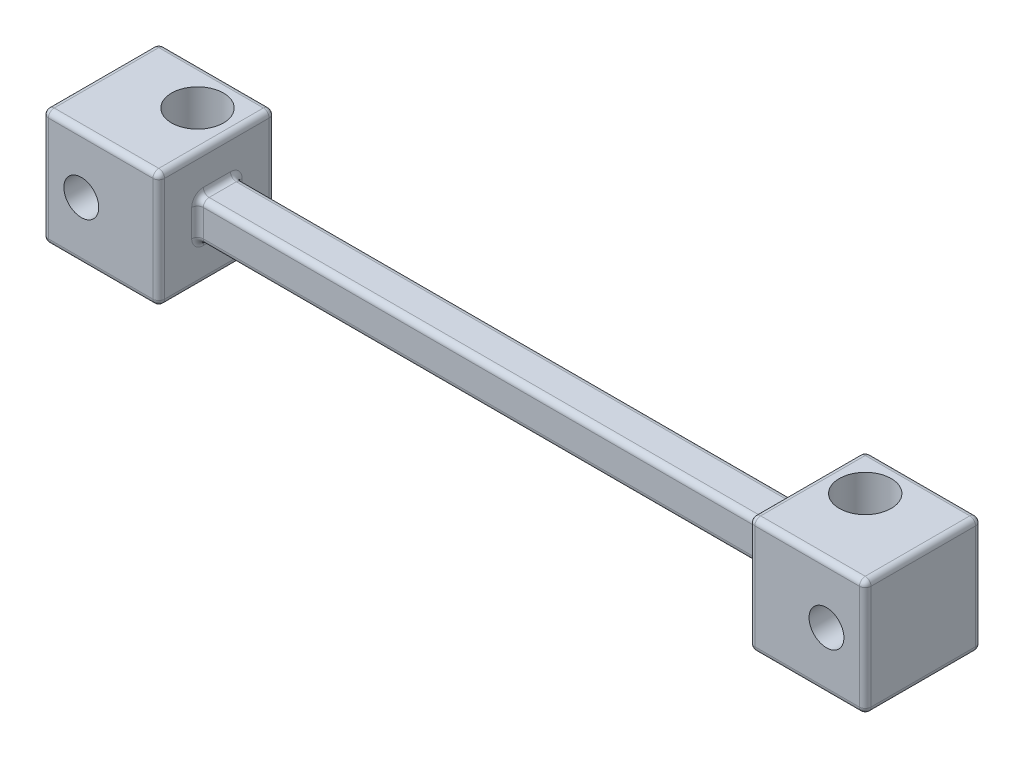
SolidWorks part; units mm, degrees
ref_plane "Front Plane" through (0, 0, 0) normal (0, 0, 1) x (1, 0, 0)
ref_plane "Top Plane" through (0, 0, 0) normal (0, 1, 0) x (1, 0, 0)
ref_plane "Right Plane" through (0, 0, 0) normal (1, 0, 0) x (0, 0, -1)
sketch "Sketch1" plane through (0, 0, 0) normal (1, 0, 0) x (0, 0, -1)
  line L1 (0, 0) -> (30, 0)
  line L2 (0, 0) -> (0, 30)
  line L3 (0, 30) -> (30, 30)
  line L4 (30, 0) -> (30, 30)
  dimension "D1" = 30
  dimension "D2" = 30
extrude "Boss-Extrude1" add sketch "Sketch1" along normal blind 20 and the other way blind 10 contours L2 L3 L4 L1
sketch "Sketch2" plane through (20, 0, 0) normal (1, 0, 0) x (0, 0, -1)
  line L0 (20, 0) -> (20, 10) construction
  line L1 (10, 20) -> (20, 20)
  line L2 (10, 20) -> (10, 10)
  line L3 (10, 10) -> (20, 10)
  line L4 (20, 20) -> (20, 10)
  line L5 (0, 0) -> (30, 0) construction
  line L6 (20, 10) -> (30, 10) construction
  line L7 (30, 0) -> (30, 30) construction
  line L8 (10, 30) -> (10, 20) construction
  line L9 (0, 30) -> (30, 30) construction
  line L10 (0, 20) -> (10, 20) construction
  line L11 (0, 0) -> (0, 30) construction
extrude "Boss-Extrude2" add sketch "Sketch2" along normal blind 152.4
sketch "Sketch3" plane through (172.4, 0, 0) normal (1, 0, 0) x (0, 0, -1)
  line L0 (18, 10) -> (18, 12) construction
  line L1 (12, 18) -> (18, 18)
  line L2 (12, 18) -> (12, 12)
  line L3 (12, 12) -> (18, 12)
  line L4 (18, 18) -> (18, 12)
  line L5 (10, 10) -> (20, 10) construction
  line L6 (18, 12) -> (20, 12) construction
  line L7 (20, 10) -> (20, 20) construction
  line L8 (10, 18) -> (12, 18) construction
  line L9 (10, 20) -> (10, 10) construction
  line L10 (12, 18) -> (12, 20) construction
  line L11 (20, 20) -> (10, 20) construction
extrude "Cut-Extrude1" cut sketch "Sketch3" against normal up to surface (152.4 mm away) up to face at (20, 15, -15)
sketch "Sketch4" plane through (0, 30, 0) normal (0, 1, 0) x (1, 0, 0)
  line L0 (20, 20) -> (10, 20) construction
  line L2 (10, 20) -> (10, 0) construction
  line L3 (-10, 0) -> (20, 0) construction
  circle A0 centre (10, 20) radius 6.7
  dimension "D1" = 20
  dimension "D2" = 13.4
extrude "Cut-Extrude2" cut sketch "Sketch4" against normal blind 15
sketch "Sketch5" plane through (0, 0, 0) normal (0, 0, 1) x (1, 0, 0)
  line L0 (20, 15) -> (0, 15) construction
  line L1 (20, 0) -> (20, 30) construction
  circle A0 centre (0, 15) radius 4.5
  dimension "D1" = 9
extrude "Cut-Extrude3" cut sketch "Sketch5" against normal blind 15
ref_plane "Plane1" through (96.2, 0, 0) normal (1, 0, 0) x (0, 0, -1)
mirror "Mirror1" about plane through (96.2, 0, 0) normal (1, 0, 0) of "Cut-Extrude2", "Cut-Extrude3", "Boss-Extrude1"
fillet "Fillet3" radius 1.5 36 edges at (172.4, 30, -15) (172.4, 15, 0) (172.4, 10, -15) (172.4, 15, -10) (96.2, 10, -10) (5, 0, 0) (-10, 30, -15) (-10, 15, 0) (-10, 0, -15) (-10, 15, -30) (5, 0, -30) (5, 30, -30) (20, 15, 0) (20, 30, -15) (20, 15, -30) (20, 0, -15) (20, 10, -15) (20, 15, -10) (96.2, 10, -20) (172.4, 15, -20) (20, 15, -20) (96.2, 20, -20) (172.4, 20, -15) (96.2, 20, -10) (20, 20, -15) (172.4, 0, -15) (187.4, 0, 0) (187.4, 30, -30) (172.4, 15, -30) (187.4, 0, -30) (202.4, 15, 0) (202.4, 30, -15) (202.4, 15, -30) (202.4, 0, -15) (5, 30, 0) (187.4, 30, 0)
